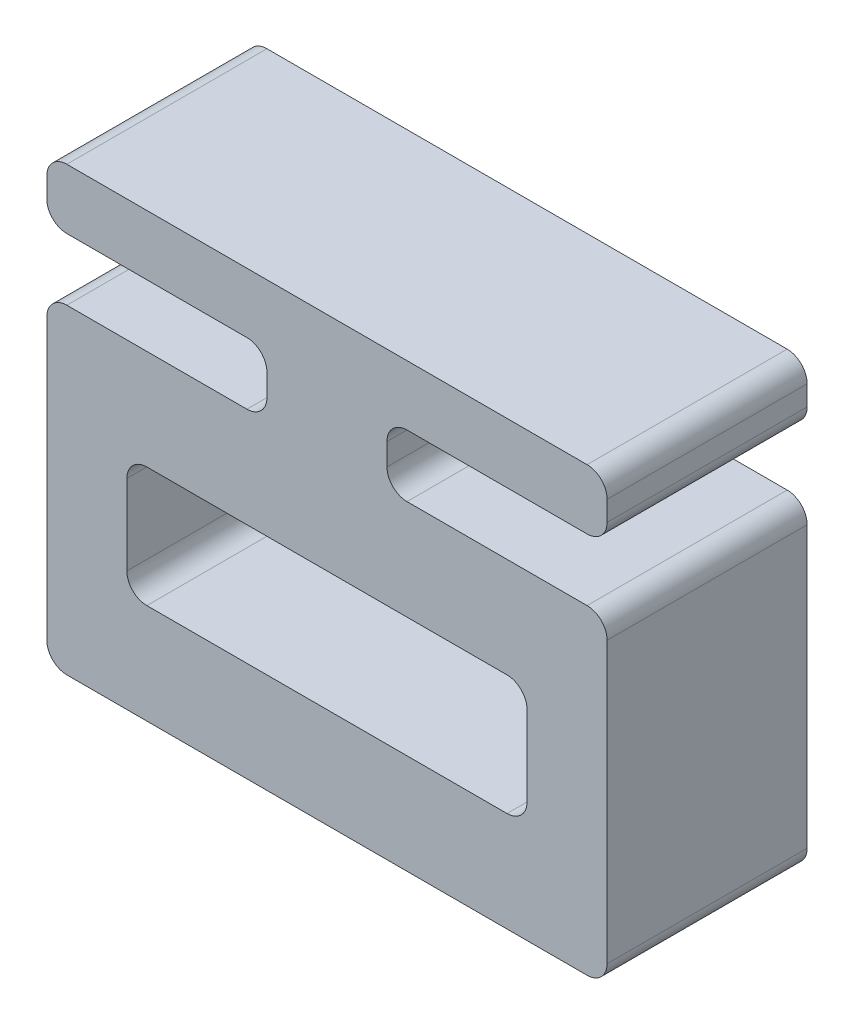
SolidWorks part; units mm, degrees
ref_plane "Front Plane" through (0, 0, 0) normal (0, 0, 1) x (1, 0, 0)
ref_plane "Top Plane" through (0, 0, 0) normal (0, 1, 0) x (1, 0, 0)
ref_plane "Right Plane" through (0, 0, 0) normal (1, 0, 0) x (0, 0, -1)
sketch "Sketch1" plane through (0, 0, 0) normal (0, 0, 1) x (1, 0, 0)
  line L0 (-5, 0) -> (5, 0) construction
  line L1 (-5, -1.5) -> (5, -1.5)
  line L2 (-5, -1.5) -> (-5, 1.5)
  line L3 (-5, 1.5) -> (5, 1.5)
  line L4 (5, -1.5) -> (5, 1.5)
  line L5 (-7, -4) -> (7, -4)
  line L6 (-7, -4) -> (-7, 4)
  line L7 (-7, 7.05) -> (7, 7.05)
  line L8 (7, -4) -> (7, 4)
  line L9 (-7, 5.55) -> (-1.5, 5.55)
  line L10 (-7, 4) -> (-1.5, 4)
  line L11 (-1.5, 5.55) -> (-1.5, 4)
  line L12 (0, 1.5) -> (0, -1.5) construction
  line L13 (-7, 5.55) -> (-7, 7.05)
  line L14 (7, 5.55) -> (7, 7.05)
  line L15 (7, 5.55) -> (1.5, 5.55)
  line L17 (7, 4) -> (1.5, 4)
  line L18 (1.5, 5.55) -> (1.5, 4)
  point P16 (0, 0)
  dimension "D1" = 10
  dimension "D2" = 2.5
  dimension "D3" = 3
  dimension "D4" = 2.5
  dimension "D5" = 1.55
  dimension "D6" = 14
  dimension "D7" = 1.5
  dimension "D8" = 3
extrude "Boss-Extrude1" add sketch "Sketch1" along normal blind 5
fillet "Fillet2" radius 0.5 16 edges at (-7, -4, 2.5) (7, -4, 2.5) (-7, 7.05, 2.5) (7, 7.05, 2.5) (7, 5.55, 2.5) (-7, 5.55, 2.5) (-7, 4, 2.5) (7, 4, 2.5) (1.5, 4, 2.5) (1.5, 5.55, 2.5) (-1.5, 5.55, 2.5) (-1.5, 4, 2.5) (5, -1.5, 2.5) (5, 1.5, 2.5) (-5, 1.5, 2.5) (-5, -1.5, 2.5)
